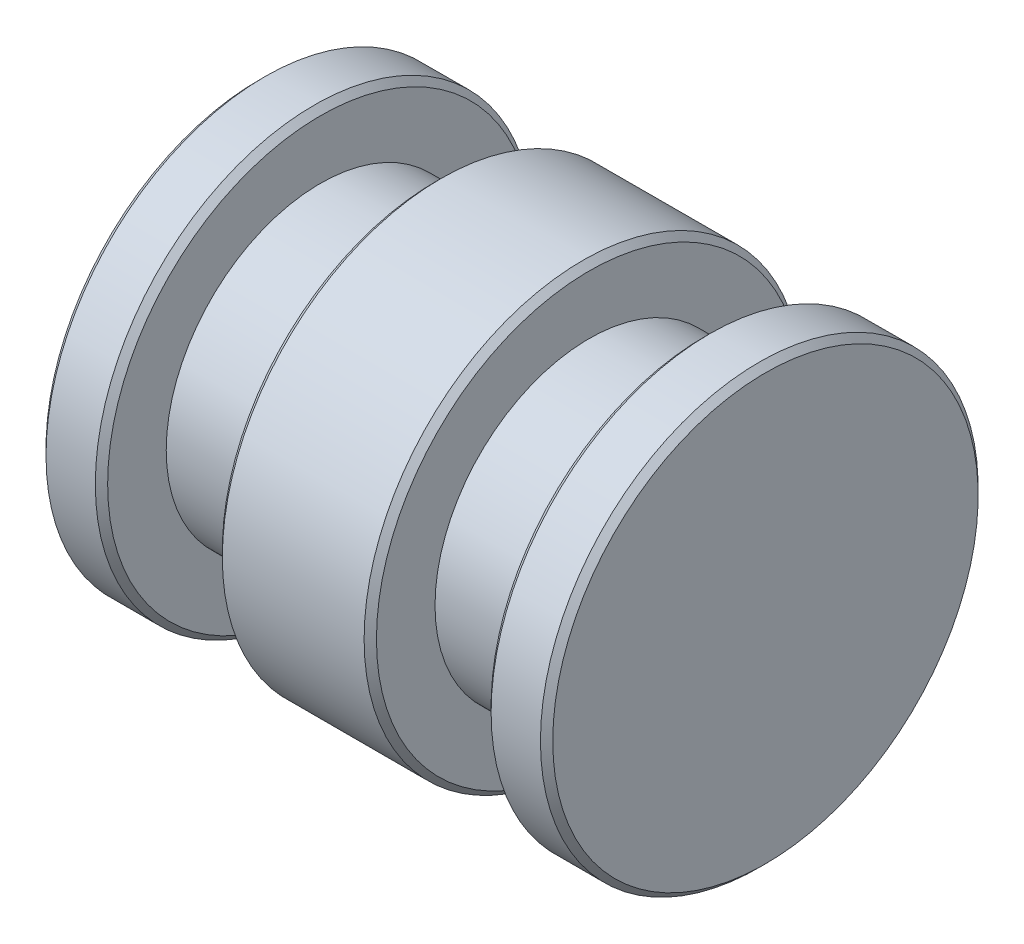
SolidWorks part; units mm, degrees
material "6063-T6"
ref_plane "Front Plane" through (0, 0, 0) normal (0, 0, 1) x (1, 0, 0)
ref_plane "Top Plane" through (0, 0, 0) normal (0, 1, 0) x (1, 0, 0)
ref_plane "Right Plane" through (0, 0, 0) normal (1, 0, 0) x (0, 0, -1)
sketch "Sketch1" plane through (0, 0, 0) normal (1, 0, 0) x (0, 0, -1)
  circle A0 centre (0, 0) radius 4.5085
  dimension "D1" = 9.017
sketch "Sketch2" plane through (0, 0, 0) normal (0, 0, 1) x (1, 0, 0)
  line L0 (-1.6174, 0) -> (23.3579, 0) construction
  line L2 (3.6322, 4.5085) -> (3.6322, 3.175)
  line L3 (3.6322, 3.175) -> (1.27, 3.175)
  line L4 (1.27, 3.175) -> (1.27, 4.5085)
  line L6 (10.4394, 5.191) -> (10.4394, -6.0436) construction
  line L13 (9.1694, 4.5085) -> (9.1694, 3.175)
  line L14 (9.1694, 3.175) -> (6.8072, 3.175)
  line L15 (6.8072, 3.175) -> (6.8072, 4.5085)
  line L16 (0, 0) -> (0, 4.5085)
  line L21 (0, -4.5085) -> (0, 4.5085) construction
  line L22 (0, 4.5085) -> (1.27, 4.5085)
  line L23 (3.6322, 4.5085) -> (6.8072, 4.5085)
  line L27 (10.4394, 0) -> (0, 0)
  line L31 (9.1694, 4.5085) -> (10.4394, 4.5085)
  line L33 (10.4394, 4.5085) -> (10.4394, 0)
  point P5 (5.2197, 4.5085)
  dimension "D1" = 3.175
  dimension "D2" = 6.35
  dimension "D3" = 2.3622
  dimension "D4" = 1.27
  dimension "D5" = 1.27
  dimension "D6" = 2.3622
  dimension "D7" = 5.2197
  dimension "D8" = 9.017
sketch "Sketch3" [suppressed] plane through (22.86, 0, 0) normal (1, 0, 0) x (0, 0, -1)
  circle A0 centre (0, 0) radius 7.9117
revolve "Revolve1" add sketch "Sketch2" angle 360 about L0
chamfer "vent-edge-break" distance 0.127 angle 45 6 edges at (9.1694, 0, 4.5085) (10.4394, 0, 4.5085) (3.6322, 0, 4.5085) (1.27, 0, 4.5085) (0, 0, 4.5085) (6.8072, 0, 4.5085)
